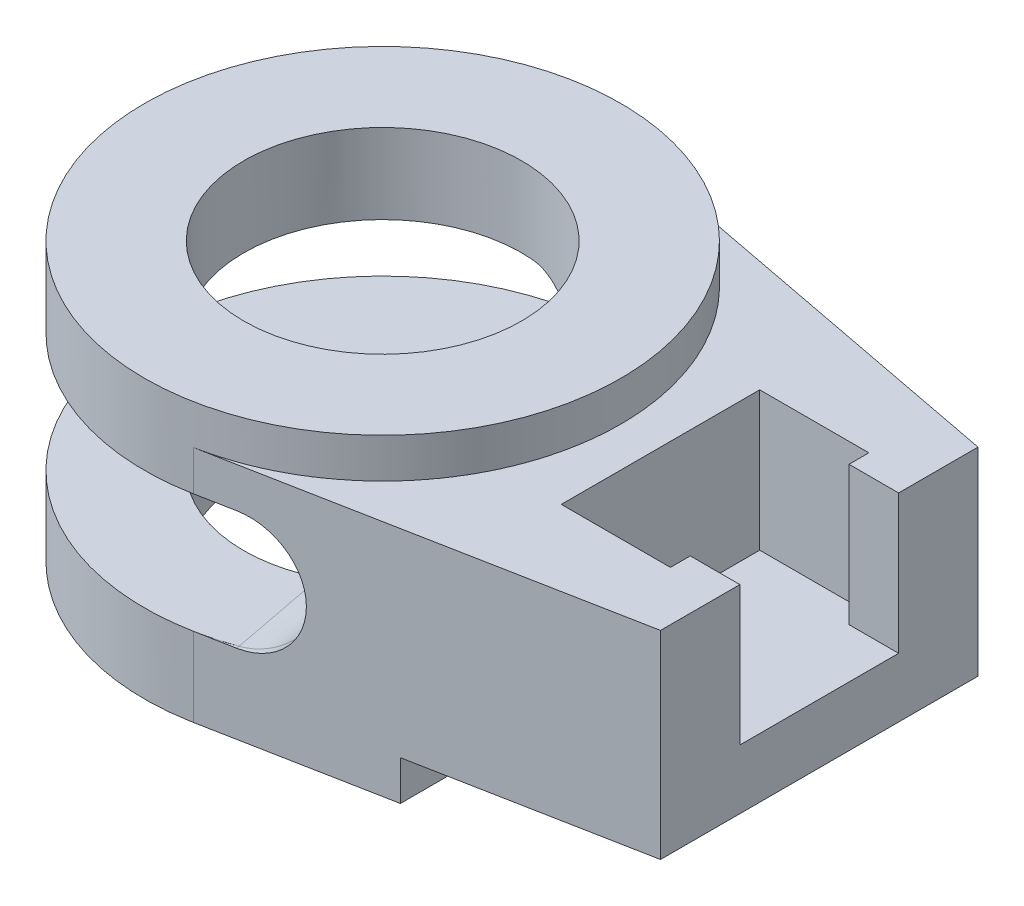
SolidWorks part; units mm, degrees
ref_plane "前基準面" through (0, 0, 0) normal (0, 0, 1) x (1, 0, 0)
ref_plane "上基準面" through (0, 0, 0) normal (0, 1, 0) x (1, 0, 0)
ref_plane "右基準面" through (0, 0, 0) normal (1, 0, 0) x (0, 0, -1)
sketch "草圖1" plane through (0, 0, 0) normal (0, 1, 0) x (1, 0, 0)
  circle A0 centre (0, 0) radius 28
  circle A1 centre (0, 0) radius 48
  dimension "D1" = 56
  dimension "D2" = 96
extrude "填料-伸長1" add sketch "草圖1" along normal blind 56
sketch "草圖2" plane through (0, 56, 0) normal (0, 1, 0) x (1, 0, 0)
  line L0 (0, 0) -> (64.0457, 0) construction
  line L1 (64.0457, 0) -> (88, 0) construction
  line L2 (88, 32) -> (88, -32)
  line L3 (88, 32) -> (9.0396, 47.1411)
  line L4 (88, -32) -> (9.0396, -47.1411)
  arc A0 (9.0396, -47.1411) -> (9.0396, 47.1411) centre (0, 0) ccw
  circle A1 centre (0, 0) radius 48 construction
  dimension "D1" = 64
extrude "填料-伸長3" add sketch "草圖2" against normal blind 56 separate body
sketch "草圖3" plane through (9.0396, 0, 47.1411) normal (0.1883, 0, 0.9821) x (0.9821, 0, -0.1883)
  line L0 (0, 48) -> (92.4518, 48)
  line L1 (0, 0) -> (0, 56) construction
  line L2 (92.4518, 0) -> (92.4518, 56) construction
  line L3 (92.4518, 48) -> (92.4518, 56)
  line L4 (92.4518, 56) -> (0, 56)
  line L5 (48, 56) -> (-48, 56) construction
  line L6 (0, 56) -> (0, 48)
  dimension "D1" = 8
extrude "除料-伸長1" cut sketch "草圖3" against normal up to next
sketch "草圖4" plane through (0, 48, 0) normal (0, 1, 0) x (1, 0, 0)
  line L0 (88, 16) -> (78, 16)
  line L1 (88, 32) -> (88, -32) construction
  line L2 (78, 16) -> (78, 20)
  line L3 (78, 20) -> (56, 20)
  line L4 (56, 20) -> (56, -20)
  line L5 (0, 0) -> (13.3291, 0) construction
  line L6 (88, -16) -> (88, 16)
  line L7 (78, -20) -> (56, -20)
  line L8 (78, -16) -> (78, -20)
  line L9 (88, -16) -> (78, -16)
  point P12 (88, 0)
  point P13 (56, 0)
  dimension "D1" = 22
  dimension "D2" = 10
  dimension "D3" = 4
  dimension "D4" = 40
extrude "除料-伸長2" cut sketch "草圖4" against normal blind 28
sketch "草圖5" plane through (9.0396, 0, 47.1411) normal (0.1883, 0, 0.9821) x (0.9821, 0, -0.1883)
  line L0 (-48, 39.9174) -> (7.4103, 39.9174)
  line L1 (-48, 56) -> (-48, 0) construction
  line L2 (7.4103, 15.9174) -> (-48, 15.9174)
  line L3 (-48, 56) -> (-48, 0) construction
  line L4 (-48, 15.9174) -> (-48, 39.9174)
  line L5 (-48, 27.9174) -> (67.4125, 27.9174) construction
  arc A0 (7.4103, 39.9174) -> (7.4103, 15.9174) centre (7.4103, 27.9174) cw
  dimension "D1" = 12
extrude "除料-伸長8" cut sketch "草圖5" against normal through all
sketch "草圖12" plane through (0, 0, 0) normal (0, 0, 1) x (1, 0, 0)
  line L0 (88, 0) -> (88, 8)
  line L1 (88, 0) -> (88, 48) construction
  line L2 (88, 8) -> (44, 8)
  line L3 (44, 8) -> (44, 0)
  line L4 (9.0396, 0) -> (88, 0) construction
  line L5 (44, 0) -> (88, 0)
  dimension "D1" = 8
  dimension "D2" = 44
extrude "除料-伸長9" cut sketch "草圖12" against normal through all and the other way through all
